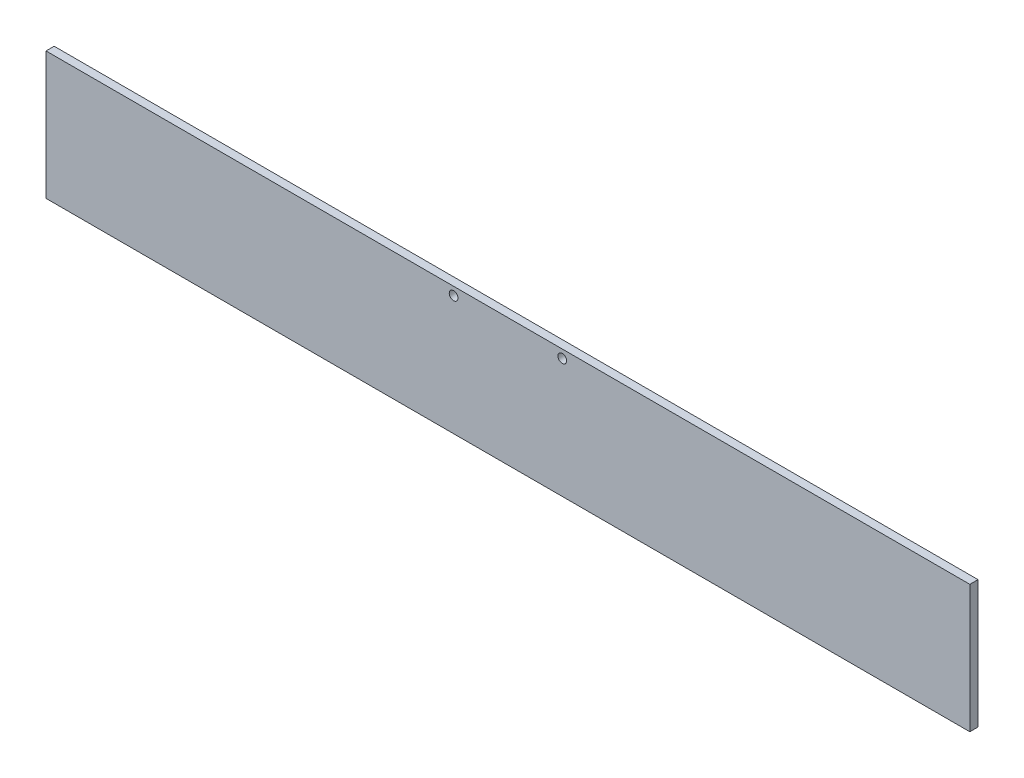
SolidWorks part; units mm, degrees
material "Perspex (TM) GS Acrylic Cast Sheet"
ref_plane "Front Plane" through (0, 0, 0) normal (0, 0, 1) x (1, 0, 0)
ref_plane "Top Plane" through (0, 0, 0) normal (0, 1, 0) x (1, 0, 0)
ref_plane "Right Plane" through (0, 0, 0) normal (1, 0, 0) x (0, 0, -1)
sketch "Sketch1" plane through (0, 0, 0) normal (0, 0, 1) x (1, 0, 0)
  line L1 (0, 0) -> (340, 0)
  line L2 (0, 0) -> (0, 47)
  line L3 (0, 47) -> (340, 47)
  line L4 (340, 0) -> (340, 47)
  dimension "D1" = 340
  dimension "D2" = 47
extrude "Boss-Extrude1" add sketch "Sketch1" along normal blind 3
sketch "Sketch2" plane through (0, 0, 0) normal (0, 0, -1) x (-1, 0, 0)
  circle A0 centre (-150, 44) radius 1.6 construction
  circle A1 centre (-190, 44) radius 1.6 construction
  circle A2 centre (-150, 44) radius 1.6
  circle A3 centre (-190, 44) radius 1.6
extrude "Cut-Extrude1" cut sketch "Sketch2" against normal up to next
